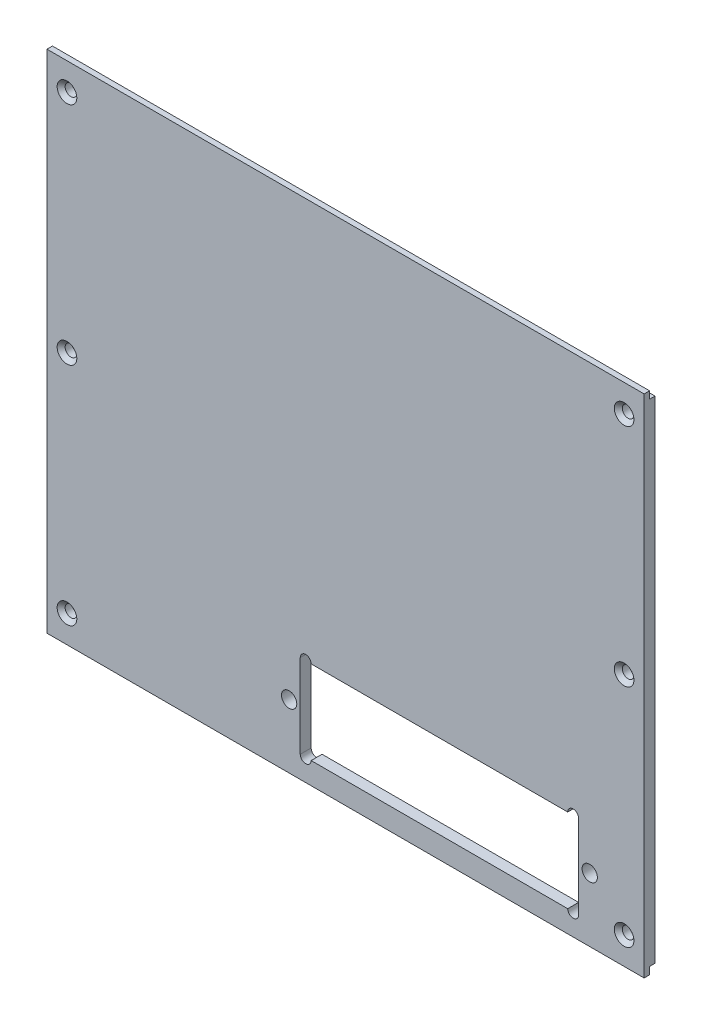
SolidWorks part; units mm, degrees
ref_plane "Front Plane" through (0, 0, 0) normal (0, 0, 1) x (1, 0, 0)
ref_plane "Top Plane" through (0, 0, 0) normal (0, 1, 0) x (1, 0, 0)
ref_plane "Right Plane" through (0, 0, 0) normal (1, 0, 0) x (0, 0, -1)
sketch "Sketch1" plane through (0, 0, 0) normal (0, 0, 1) x (1, 0, 0)
  line L0 (-82.55, -78) -> (-82.55, 78) construction
  line L1 (-82.05, -69.5) -> (82.05, -69.5)
  line L2 (-82.05, -69.5) -> (-82.05, 69.5)
  line L3 (-82.05, 69.5) -> (82.05, 69.5)
  line L4 (82.05, -69.5) -> (82.05, 69.5)
  line L6 (82.55, 78) -> (82.55, -78) construction
  line L7 (82.55, 70) -> (-82.55, 70) construction
  line L8 (-82.55, -70) -> (82.55, -70) construction
  dimension "D1" = 0.5
  dimension "D2" = 0.5
  dimension "D3" = 0.5
  dimension "D4" = 0.5
extrude "Boss-Extrude1" add sketch "Sketch1" along normal blind 3
hole_wizard "CSK for #4 Flat Head Machine Screw (100)1" positions "Sketch3" profile "Sketch2" countersink size "#4" standard "ANSI Inch" end condition up to next
sketch "Sketch3" plane through (0, 0, 3) normal (0, 0, 1) x (1, 0, 0)
  point P0 (-76.55, 62)
  point P3 (-76.55, 0)
  point P6 (-76.55, -62)
  point P9 (76.55, -62)
  point P12 (76.55, 0)
  point P15 (76.55, 62)
sketch "Sketch2" plane through (-76.55, 62, 3) normal (1, 0, 0) x (0, -1, 0)
  line L0 (0, 0) -> (0, 3)
  line L1 (0, 3) -> (1.6, 3)
  line L2 (1.6, 3) -> (1.6, 1.1)
  line L3 (1.6, 1.1) -> (2.7, 0)
  line L5 (2.7, 0) -> (0, 0)
  line L6 (-1.6, 1.1) -> (-2.7, 0) construction
  line L11 (0, -6.35) -> (0, 107.95) construction
  dimension "Thru Hole Dia." = 3.2
  dimension "Thru Hole Depth" = 3
  dimension "Near C'Sink Dia." = 5.4
  dimension "Near C'Sink Angle" = 90
sketch "Sketch4" plane through (0, 0, 3) normal (0, 0, 1) x (1, 0, 0)
  line L0 (-82.05, -69.5) -> (82.05, -69.5) construction
  line L1 (-12.45, -40.5) -> (64.05, -40.5)
  line L2 (-12.45, -40.5) -> (-12.45, -63.5)
  line L3 (-12.45, -63.5) -> (64.05, -63.5)
  line L4 (64.05, -40.5) -> (64.05, -63.5)
  line L5 (82.05, -69.5) -> (82.05, 69.5) construction
  line L6 (25.8, -63.5) -> (25.8, -40.5) construction
  circle A4 centre (-15.5, -52) radius 2.1
  circle A5 centre (67.1, -52) radius 2.1
  point P20 (25.8, -52)
  dimension "D6" = 4.2
  dimension "D7" = 82.6
  dimension "D2" = 76.5
  dimension "D3" = 23
  dimension "D4" = 6
  dimension "D5" = 18
extrude "Cut-Extrude1" cut sketch "Sketch4" against normal up to next
sketch "Sketch5" plane through (0, 0, 3) normal (0, 0, 1) x (1, 0, 0)
  line L0 (-10.95, -63.5) -> (-10.95, -40.5) construction
  line L1 (-12.45, -63.5) -> (64.05, -63.5) construction
  line L2 (64.05, -40.5) -> (-12.45, -40.5) construction
  line L3 (-12.45, -63.5) -> (-12.45, -40.5)
  line L4 (-9.45, -63.5) -> (-9.45, -40.5)
  line L5 (25.8, -63.5) -> (25.8, -40.5) construction
  line L6 (-12.45, -40.5) -> (-12.45, -63.5) construction
  line L7 (62.55, -63.5) -> (62.55, -40.5) construction
  line L8 (64.05, -63.5) -> (64.05, -40.5)
  line L9 (61.05, -63.5) -> (61.05, -40.5)
  arc A0 (-12.45, -63.5) -> (-9.45, -63.5) centre (-10.95, -63.5) ccw
  arc A1 (-9.45, -40.5) -> (-12.45, -40.5) centre (-10.95, -40.5) ccw
  arc A2 (64.05, -63.5) -> (61.05, -63.5) centre (62.55, -63.5) cw
  arc A3 (61.05, -40.5) -> (64.05, -40.5) centre (62.55, -40.5) cw
  point P6 (-10.95, -52)
  point P17 (62.55, -52)
  dimension "D1" = 3
extrude "Cut-Extrude2" cut sketch "Sketch5" against normal up to next
sketch "Sketch6" plane through (0, 0, 0) normal (0, 0, -1) x (-1, 0, 0)
  line L0 (82.05, 69.5) -> (82.05, -69.5) construction
  line L1 (-82.05, 69.5) -> (82.05, 69.5)
  line L2 (-82.05, 69.5) -> (-82.05, 67.5)
  line L3 (-82.05, 67.5) -> (82.05, 67.5)
  line L4 (82.05, 69.5) -> (82.05, 67.5)
  line L6 (-82.05, -69.5) -> (82.05, -69.5)
  line L7 (-82.05, -69.5) -> (-82.05, -67.5)
  line L8 (-82.05, -67.5) -> (82.05, -67.5)
  line L9 (82.05, -69.5) -> (82.05, -67.5)
  dimension "D1" = 2
  dimension "D2" = 2
extrude "Cut-Extrude3" cut sketch "Sketch6" against normal blind 1.5
